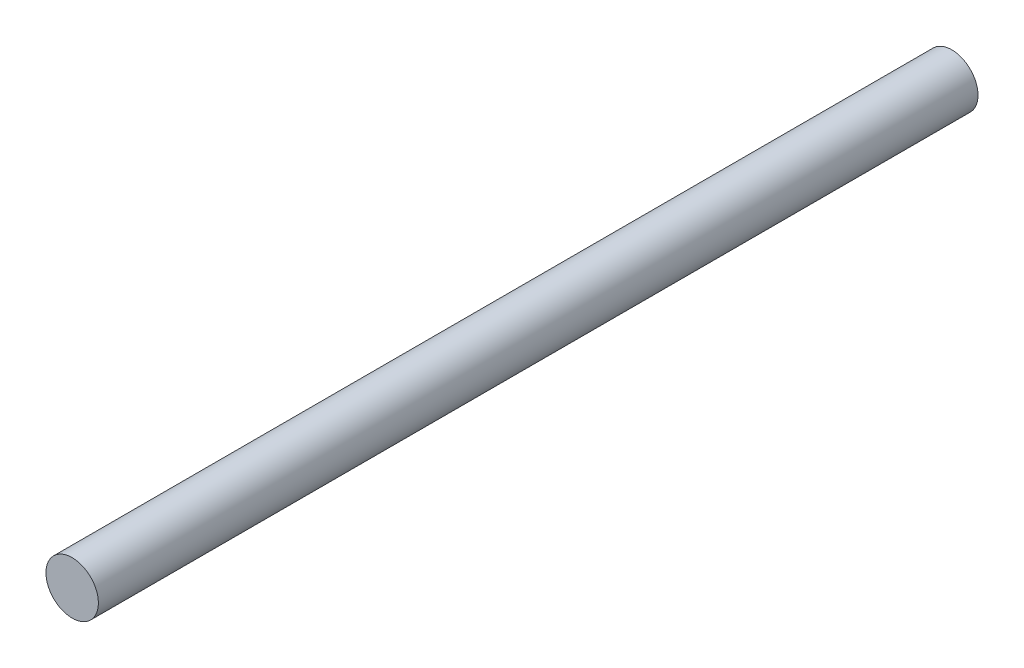
SolidWorks part; units mm, degrees
ref_plane "Front Plane" through (0, 0, 0) normal (0, 0, 1) x (1, 0, 0)
ref_plane "Top Plane" through (0, 0, 0) normal (0, 1, 0) x (1, 0, 0)
ref_plane "Right Plane" through (0, 0, 0) normal (1, 0, 0) x (0, 0, -1)
sketch "Sketch1" plane through (0, 0, 0) normal (0, 0, 1) x (1, 0, 0)
  circle A0 centre (0, 0) radius 2
  dimension "D1" = 4
extrude "Boss-Extrude1" add sketch "Sketch1" along normal mid plane 67.1
